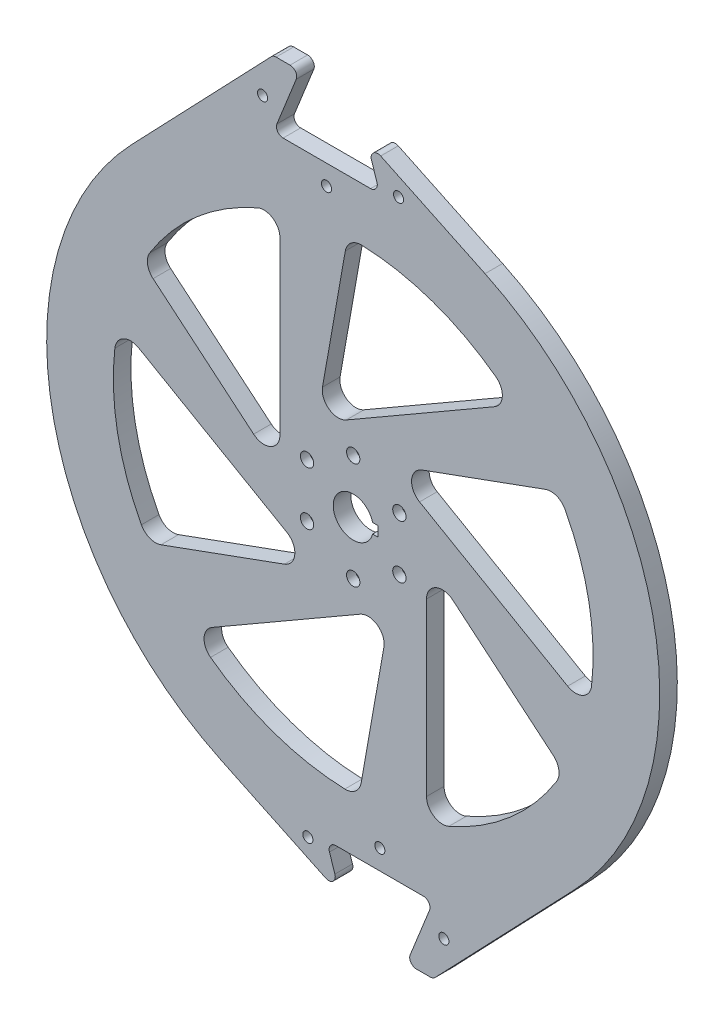
SolidWorks part; units mm, degrees
material "Titanium"
ref_plane "Front Plane" through (0, 0, 0) normal (0, 0, 1) x (1, 0, 0)
ref_plane "Top Plane" through (0, 0, 0) normal (0, 1, 0) x (1, 0, 0)
ref_plane "Right Plane" through (0, 0, 0) normal (1, 0, 0) x (0, 0, -1)
sketch "Sketch1" plane through (0, 0, 0) normal (0, 0, 1) x (1, 0, 0)
  line L0 (-105.5344, 100.9609) -> (-38.1, 171.45)
  line L1 (-38.1, 171.45) -> (-25.4, 171.45)
  line L2 (62.8112, 131.8536) -> (6.35, 158.75)
  line L3 (105.5344, -100.9609) -> (38.1, -171.45)
  line L4 (38.1, -171.45) -> (25.4, -171.45)
  line L5 (-62.8112, -131.8536) -> (-6.35, -158.75)
  line L6 (6.35, 158.75) -> (12.7, 139.7)
  line L7 (12.7, 139.7) -> (-38.1, 139.7)
  line L8 (-25.4, 171.45) -> (-38.1, 139.7)
  line L9 (-6.35, -158.75) -> (-12.7, -139.7)
  line L10 (25.4, -171.45) -> (38.1, -139.7)
  line L11 (38.1, -139.7) -> (-12.7, -139.7)
  arc A0 (-105.5344, 100.9609) -> (-62.8112, -131.8536) centre (0, 0) ccw
  arc A1 (62.8112, 131.8536) -> (105.5344, -100.9609) centre (0, 0) cw
  dimension "D3" = 146.05
  dimension "D4" = 146.05
  dimension "D1" = 12.7
  dimension "D2" = 31.75
  dimension "D5" = 50.8
  dimension "D6" = 12.7
  dimension "D7" = 38.1
  dimension "D8" = 50.8
  dimension "D9" = 31.75
  dimension "D10" = 19.05
  dimension "D11" = 158.75
  dimension "D12" = 12.7
  dimension "D13" = 31.75
  dimension "D14" = 38.1
  dimension "D15" = 31.75
  dimension "D16" = 19.05
  dimension "D17" = 158.75
  dimension "D18" = 12.7
extrude "Extrude1" add sketch "Sketch1" along normal mid plane 8.382
sketch "Sketch2" plane through (0, 0, 4.191) normal (0, 0, 1) x (1, 0, 0)
  circle A0 centre (0, 0) radius 9.525
  circle A1 centre (0, 25.4) radius 3.175
  dimension "D1" = 19.05
  dimension "D2" = 6.35
  dimension "D3" = 25.4
extrude "Cut-Extrude1" cut sketch "Sketch2" against normal through all
pattern_circular "CirPattern1" count 6 over 360 about axis through (0, 0, 0) along (0, 0, 1) of "Cut-Extrude1"
sketch "Sketch4" plane through (0, 0, 4.191) normal (0, 0, 1) x (1, 0, 0)
  line L0 (-34.925, 97.8292) -> (-34.925, 16.3411)
  line L1 (-47.443, 10.5039) -> (-95.3584, 50.7096)
  arc A0 (-45.5839, 104.817) -> (-96.9218, 60.5859) centre (0, 0) ccw
  arc A1 (-34.925, 16.3411) -> (-47.443, 10.5039) centre (-42.545, 16.3411) cw
  arc A2 (-96.9218, 60.5859) -> (-95.3584, 50.7096) centre (-90.4603, 56.5469) ccw
  arc A3 (-45.5839, 104.817) -> (-34.925, 97.8292) centre (-42.545, 97.8292) cw
  point P9 (-34.925, 0)
  dimension "D1" = 114.3
  dimension "D4" = 7.62
  dimension "D2" = 34.925
  dimension "D3" = 50
extrude "Cut-Extrude2" cut sketch "Sketch4" against normal through all
pattern_circular "CirPattern2" count 6 over 360 about axis through (0, 0, 0) along (0, 0, 1) of "Cut-Extrude2"
sketch "Sketch5" plane through (0, 0, 4.191) normal (0, 0, 1) x (1, 0, 0)
  line L2 (12.7, 139.7) -> (-38.1, 139.7) construction
  circle A0 centre (21.59, 142.875) radius 2.413
  circle A1 centre (-12.7, 130.175) radius 2.413
  circle A2 centre (-43.18, 152.4) radius 2.413
  dimension "D5" = 4.826
  dimension "D6" = 4.826
  dimension "D7" = 4.826
  dimension "D1" = 12.7
  dimension "D2" = 30.48
  dimension "D3" = 9.525
  dimension "D4" = 34.29
  dimension "D8" = 3.175
  dimension "D9" = 25.4
extrude "Cut-Extrude3" cut sketch "Sketch5" against normal through all
sketch "Sketch6" plane through (0, 0, 4.191) normal (0, 0, 1) x (1, 0, 0)
  line L0 (22.225, 144.3491) -> (22.225, 134.9511)
  line L1 (15.875, 128.6011) -> (-28.575, 128.6011)
  line L2 (-34.925, 134.9511) -> (-34.925, 174.7688)
  line L3 (-38.1, 171.45) -> (-105.5344, 100.9609) construction
  line L4 (-34.925, 174.7688) -> (-22.225, 160.6051)
  line L5 (-22.225, 160.6051) -> (-22.225, 144.3491)
  line L6 (-22.225, 144.3491) -> (22.225, 144.3491)
  arc A0 (-28.575, 128.6011) -> (-34.925, 134.9511) centre (-28.575, 134.9511) cw
  arc A1 (22.225, 134.9511) -> (15.875, 128.6011) centre (15.875, 134.9511) cw
  point P13 (-34.925, 128.6011)
  point P16 (22.225, 128.6011)
  dimension "D3" = 6.35
  dimension "D1" = 15.748
  dimension "D2" = 57.15
extrude "Cut-Extrude4" [suppressed] cut sketch "Sketch6" against normal blind 1.016
pattern_circular "CirPattern3" count 2 over 180 about axis through (0, 0, 0) along (0, 0, 1) of "Cut-Extrude3", "Cut-Extrude4"
mirror "Mirror1" about plane through (0, 0, 0) normal (0, 0, 1) of "CirPattern3"
sketch "Sketch7" plane through (0, 0, 4.191) normal (0, 0, 1) x (1, 0, 0)
  line L1 (11.9062, 2.3813) -> (7.1437, 2.3813)
  line L2 (11.9062, 2.3813) -> (11.9062, -2.3812)
  line L3 (11.9062, -2.3812) -> (7.1438, -2.3812)
  line L4 (7.1437, 2.3813) -> (7.1438, -2.3812)
  dimension "D1" = 4.7625
  dimension "D2" = 4.7625
  dimension "D3" = 11.9062
  dimension "D4" = 2.3813
extrude "Cut-Extrude5" cut sketch "Sketch7" against normal through all
sketch "Sketch8" plane through (0, 0, -4.191) normal (0, 0, -1) x (-1, 0, 0)
  circle A0 centre (0, 25.4) radius 6.7437
  circle A1 centre (-21.997, 12.7) radius 6.7437
  circle A2 centre (21.997, 12.7) radius 6.7437
  circle A3 centre (21.997, -12.7) radius 6.7437
  circle A4 centre (0, -25.4) radius 6.7437
  circle A5 centre (-21.997, -12.7) radius 6.7437
  dimension "D1" = 13.4874
extrude "Cut-Extrude6" cut sketch "Sketch8" against normal through all draft 41
fillet "Fillet1" radius 3.175 10 edges at (6.35, 158.75, 0) (12.7, 139.7, 0) (-38.1, 139.7, 0) (-25.4, 171.45, 0) (-38.1, 171.45, 0) (-6.35, -158.75, 0) (-12.7, -139.7, 0) (38.1, -139.7, 0) (25.4, -171.45, 0) (38.1, -171.45, 0)
